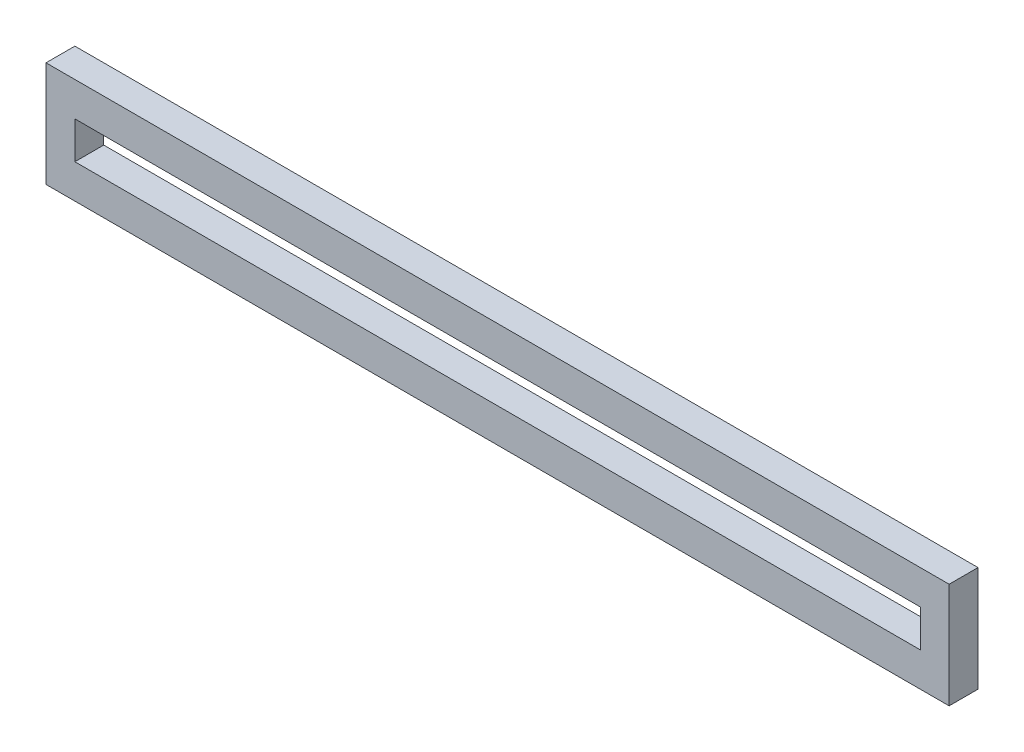
SolidWorks part; units mm, degrees
ref_plane "Front Plane" through (0, 0, 0) normal (0, 0, 1) x (1, 0, 0)
ref_plane "Top Plane" through (0, 0, 0) normal (0, 1, 0) x (1, 0, 0)
ref_plane "Right Plane" through (0, 0, 0) normal (1, 0, 0) x (0, 0, -1)
sketch "Sketch1" plane through (0, 0, 0) normal (0, 0, 1) x (1, 0, 0)
  line L0 (0, 0) -> (39.7306, 0) construction
  line L1 (0, -9.27) -> (-39.7306, -9.27) construction
  line L2 (25.4, -9.27) -> (-25.4, -9.27) construction
  line L3 (0, -3) -> (-39.7306, -3) construction
  line L4 (-25.4, -3) -> (25.4, -3) construction
  line L5 (-39.7306, -3) -> (-39.7306, -9.27) construction
  line L6 (0, -6.27) -> (39.7306, -6.27) construction
  line L7 (25.4, -6.27) -> (-25.4, -6.27) construction
  line L8 (39.7306, -6.27) -> (39.7306, 0) construction
  line L9 (-39.7306, 0) -> (-37.1906, 0) construction
  line L10 (39.7306, 0) -> (-39.7306, 0)
  line L11 (39.7306, 0) -> (39.7306, -3)
  line L12 (37.1906, -3) -> (-37.1906, -3)
  line L13 (-39.7306, 0) -> (-39.7306, -6.27)
  line L14 (-39.7306, -9.27) -> (39.7306, -9.27)
  line L15 (-39.7306, -9.27) -> (-39.7306, -6.27)
  line L16 (-37.1906, -6.27) -> (37.1906, -6.27)
  line L17 (39.7306, -9.27) -> (39.7306, -3)
  line L18 (-37.1906, 0) -> (-37.1906, -3) construction
  line L19 (-37.1906, -3) -> (-37.1906, -6.27)
  line L20 (39.7306, 0) -> (37.1906, 0) construction
  line L21 (37.1906, 0) -> (37.1906, -3) construction
  line L22 (37.1906, -3) -> (37.1906, -6.27)
  dimension "D1" = 0
  dimension "D2" = 0
  dimension "D3" = 2.54
  dimension "D4" = 2.54
extrude "Boss-Extrude1" add sketch "Sketch1" along normal blind 2.54
